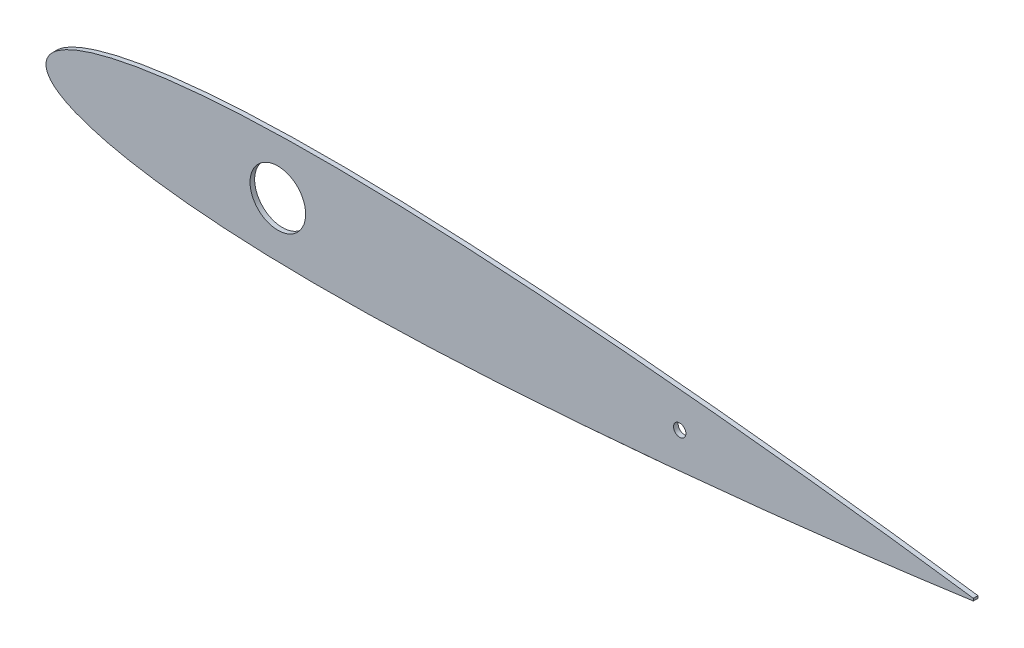
SolidWorks part; units mm, degrees
material "Oak"
ref_plane "Front Plane" through (0, 0, 0) normal (0, 0, 1) x (1, 0, 0)
ref_plane "Top Plane" through (0, 0, 0) normal (0, 1, 0) x (1, 0, 0)
ref_plane "Right Plane" through (0, 0, 0) normal (1, 0, 0) x (0, 0, -1)
sketch "Sketch5" plane through (0, 0, 0) normal (0, 0, 1) x (1, 0, 0)
  line L1 (300, 0.378) -> (300, -0.378)
  spline S1 degree 3 poles (300, 0.378) (299.2704, 0.4794) (297.2347, 0.7625) (293.6597, 1.2577) (289.1124, 1.8742) (284.0808, 2.5445) (278.752, 3.2381) (273.2659, 3.9349) (267.706, 4.629) (262.1146, 5.3131) (256.5083, 5.9822) (250.8917, 6.638) (245.2696, 7.2818) (239.6473, 7.9122) (234.0251, 8.527) (228.3991, 9.1262) (222.7683, 9.7131) (217.1359, 10.2875) (211.5054, 10.8469) (205.8776, 11.3916) (200.2515, 11.9209) (194.6264, 12.4346) (189.0028, 12.9319) (183.3815, 13.4131) (177.7632, 13.8764) (172.1483, 14.3212) (166.5375, 14.7478) (160.9317, 15.1542) (155.3317, 15.5391) (149.7375, 15.9026) (144.1487, 16.2418) (138.5657, 16.5574) (132.9909, 16.8474) (127.4274, 17.1102) (121.8776, 17.3439) (116.3408, 17.5453) (110.8155, 17.7127) (105.3013, 17.8445) (99.8006, 17.9401) (94.3174, 17.9966) (88.8558, 18.0101) (83.4186, 17.9792) (78.0085, 17.8992) (72.6285, 17.767) (67.2827, 17.5794) (61.9774, 17.3315) (56.7207, 17.021) (51.5252, 16.641) (46.4082, 16.1902) (41.3942, 15.6617) (36.5157, 15.054) (31.819, 14.3656) (27.3662, 13.6035) (23.2352, 12.7826) (19.5026, 11.9203) (16.2183, 11.0446) (13.3892, 10.1751) (10.9849, 9.3335) (8.9616, 8.5221) (7.2673, 7.747) (5.8461, 7.0106) (4.6477, 6.3006) (3.6282, 5.6065) (2.7519, 4.9266) (2.0063, 4.2499) (1.3906, 3.5703) (0.901, 2.8909) (0.5293, 2.2202) (0.2605, 1.5665) (0.0857, 0.931) (-0.0035, 0.309) (-0.0035, -0.309) (0.0857, -0.931) (0.2605, -1.5665) (0.5293, -2.2202) (0.901, -2.8909) (1.3906, -3.5703) (2.0063, -4.2499) (2.7519, -4.9266) (3.6282, -5.6065) (4.6477, -6.3006) (5.8461, -7.0106) (7.2673, -7.747) (8.9616, -8.5221) (10.9849, -9.3335) (13.3892, -10.1751) (16.2183, -11.0446) (19.5026, -11.9203) (23.2352, -12.7826) (27.3661, -13.6036) (31.8191, -14.3651) (36.5156, -15.0541) (41.3942, -15.6616) (46.4082, -16.1902) (51.5252, -16.641) (56.7207, -17.021) (61.9774, -17.3315) (67.2827, -17.5794) (72.6285, -17.767) (78.0085, -17.8992) (83.4186, -17.9792) (88.8558, -18.0101) (94.3174, -17.9966) (99.8006, -17.9401) (105.3013, -17.8445) (110.8155, -17.7127) (116.3408, -17.5453) (121.8776, -17.3439) (127.4274, -17.1102) (132.9909, -16.8474) (138.5657, -16.5574) (144.1487, -16.2418) (149.7375, -15.9026) (155.3317, -15.5391) (160.9317, -15.1542) (166.5375, -14.7478) (172.1483, -14.3212) (177.7632, -13.8764) (183.3815, -13.4131) (189.0028, -12.9319) (194.6264, -12.4346) (200.2515, -11.9209) (205.8776, -11.3916) (211.5054, -10.8469) (217.1359, -10.2875) (222.7683, -9.7131) (228.3991, -9.1262) (234.0251, -8.527) (239.6473, -7.9122) (245.2696, -7.2818) (250.8917, -6.638) (256.5083, -5.9822) (262.1146, -5.3131) (267.706, -4.629) (273.2659, -3.9349) (278.752, -3.2381) (284.0808, -2.5445) (289.1124, -1.8742) (293.6597, -1.2577) (297.2347, -0.7625) (299.2704, -0.4794) (300, -0.378) knots 0 0 0 0 0.003612 0.010079 0.017699 0.026115 0.034971 0.04405 0.053234 0.062448 0.071674 0.080921 0.090178 0.099424 0.108664 0.117912 0.12717 0.136427 0.145675 0.154916 0.164153 0.173387 0.182616 0.191838 0.201053 0.21026 0.219459 0.228647 0.237822 0.246985 0.256137 0.265279 0.274407 0.283512 0.292592 0.301646 0.310682 0.319699 0.328695 0.33766 0.346589 0.355477 0.364323 0.373122 0.381868 0.390553 0.399166 0.40769 0.416098 0.424355 0.432412 0.440205 0.447631 0.454564 0.460855 0.466413 0.471229 0.475366 0.478901 0.481915 0.484499 0.486747 0.488741 0.490543 0.492182 0.493673 0.495032 0.496279 0.497425 0.49849 0.499503 0.500497 0.50151 0.502575 0.503721 0.504968 0.506327 0.507818 0.509457 0.511259 0.513253 0.515501 0.518085 0.521099 0.524634 0.528771 0.533587 0.539145 0.545436 0.55237 0.559795 0.567588 0.575645 0.583902 0.59231 0.600834 0.609447 0.618132 0.626878 0.635677 0.644523 0.653411 0.66234 0.671305 0.680301 0.689318 0.698354 0.707408 0.716488 0.725593 0.734721 0.743863 0.753015 0.762178 0.771353 0.780541 0.78974 0.798947 0.808162 0.817384 0.826613 0.835847 0.845084 0.854325 0.863573 0.87283 0.882088 0.891336 0.900576 0.909822 0.919079 0.928326 0.937552 0.946766 0.95595 0.965029 0.973885 0.982301 0.989921 0.996388 1 1 1 1
  dimension "Tail chord" = 300
extrude "Boss-Extrude1" add sketch "Sketch5" along normal blind 1.5
ref_plane "Plane1" through (0, 0, 1.5) normal (0, 0, 1) x (1, 0, 0)
sketch "Sketch7" plane through (0, 0, 1.5) normal (0, 0, 1) x (1, 0, 0)
  line L0 (-6.7213, 0) -> (341.1075, 0) construction
  line L1 (300, -35.2391) -> (300, 43.1318) construction
  line L2 (300, -0.378) -> (300, 0.378) construction
  line L3 (0, 36.9496) -> (0, -37.0407) construction
  circle A0 centre (75, 0) radius 9
  dimension "D1" = 18
  dimension "Tail chord quarter" = 75
extrude "Cut-Extrude7" cut sketch "Sketch7" against normal through all
curve "Curve6"
  spline degree 3 poles (298.242, -0.1932, 0) (300.4407, 0, 0) (298.242, 0.1932, 0) (296.4349, 0.5367, 0) (292.0253, 1.0976, 0) (286.5771, 1.8592, 0) (279.4156, 2.8001, 0) (270.9173, 3.8949, 0) (261.066, 5.1159, 0) (250.0071, 6.4339, 0) (237.8495, 7.8187, 0) (224.7304, 9.2395, 0) (210.7923, 10.6647, 0) (196.1883, 12.0613, 0) (181.0783, 13.3946, 0) (165.6277, 14.6278, 0) (150.0058, 15.7225, 0) (134.3834, 16.6392, 0) (118.9317, 17.3387, 0) (103.8195, 17.7845, 0) (89.2123, 17.9443, 0) (75.2698, 17.7935, 0) (62.1444, 17.3161, 0) (49.9793, 16.5075, 0) (38.907, 15.374, 0) (29.0471, 13.9333, 0) (20.5034, 12.2128, 0) (13.3641, 10.246, 0) (7.6828, 8.0707, 0) (3.4992, 5.7028, 0) (0.7348, 3.1014, 0) (-0.3264, 0, 0) (0.7348, -3.1014, 0) (3.4992, -5.7028, 0) (7.6828, -8.0707, 0) (13.3641, -10.246, 0) (20.5034, -12.2128, 0) (29.0471, -13.9333, 0) (38.907, -15.374, 0) (49.9793, -16.5075, 0) (62.1444, -17.3161, 0) (75.2698, -17.7935, 0) (89.2123, -17.9443, 0) (103.8195, -17.7845, 0) (118.9317, -17.3387, 0) (134.3834, -16.6392, 0) (150.0058, -15.7225, 0) (165.6277, -14.6278, 0) (181.0783, -13.3946, 0) (196.1883, -12.0613, 0) (210.7923, -10.6647, 0) (224.7304, -9.2395, 0) (237.8495, -7.8187, 0) (250.0071, -6.4339, 0) (261.066, -5.1159, 0) (270.9173, -3.8949, 0) (279.4156, -2.8001, 0) (286.5771, -1.8592, 0) (292.0253, -1.0976, 0) (296.4349, -0.5367, 0) (298.242, -0.1932, 0) (300.4407, 0, 0) (298.242, 0.1932, 0) knots -0.012119 -0.005412 -0.001357 0 0.001357 0.005412 0.012119 0.021403 0.033159 0.047255 0.063534 0.081814 0.101892 0.123547 0.146538 0.170613 0.195504 0.220938 0.246636 0.272314 0.297694 0.3225 0.346466 0.36934 0.390884 0.410879 0.429129 0.445462 0.459736 0.471848 0.481751 0.489494 0.495334 0.5 0.504666 0.510506 0.518249 0.528152 0.540264 0.554538 0.570871 0.589121 0.609116 0.63066 0.653534 0.6775 0.702306 0.727686 0.753364 0.779062 0.804496 0.829387 0.853462 0.876453 0.898108 0.918186 0.936466 0.952745 0.966841 0.978597 0.987881 0.994588 0.998643 1 1.001357 1.005412 1.012119 periodic
sketch "Sketch13" plane through (0, 0, 0) normal (0, 0, 1) x (1, 0, 0)
  circle A0 centre (205, 0) radius 2
  dimension "D1" = 4
  dimension "Small hole" = 205
extrude "Cut-Extrude11" cut sketch "Sketch13" along normal through all
sketch "Sketch14" plane through (0, 0, 1.5) normal (0, 0, 1) x (1, 0, 0)
  circle A0 centre (205, 0) radius 2
  dimension "D1" = 4
  dimension "anti rotation peg" = 205
equation "\"Tail chord quarter@Sketch7\" = \"Tail chord@Sketch5\" * 0.25"
equation "\"Elevator length\"= 50mm'Elevator cut"
equation "\"Small hole@Sketch13\"=\"Tail chord quarter@Sketch7\"*3-20"
equation "\"anti rotation peg@Sketch14\"=\"Small hole@Sketch13\""
equation "\"Chord\"= 300mm'Tail chord"
equation "\"Tail chord@Sketch5\"=\"Chord\""
